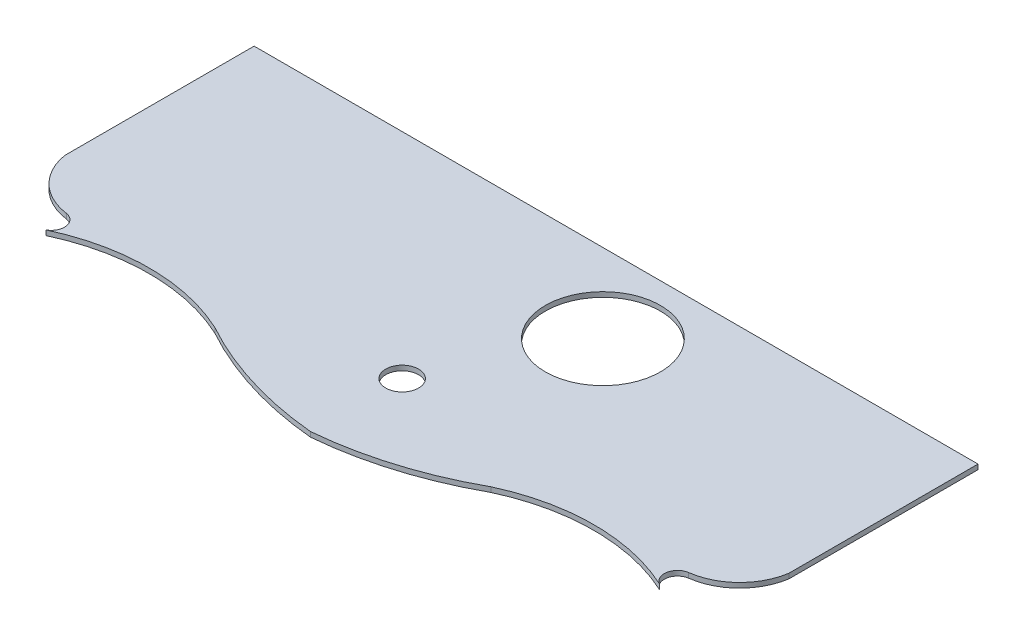
SolidWorks part; units mm, degrees
ref_plane "Front Plane" through (0, 0, 0) normal (0, 0, 1) x (1, 0, 0)
ref_plane "Top Plane" through (0, 0, 0) normal (0, 1, 0) x (1, 0, 0)
ref_plane "Right Plane" through (0, 0, 0) normal (1, 0, 0) x (0, 0, -1)
ref_plane "Plane1" through (0, 22.5, 0) normal (0, 1, 0) x (1, 0, 0)
ref_plane "Plane2" through (0, 24, 0) normal (0, 1, 0) x (1, 0, 0)
sketch "Sketch2" plane through (0, 22.5, 0) normal (0, 1, 0) x (1, 0, 0)
  line L0 (0, -100) -> (0, 70) construction
  line L15 (-34.8399, -30) -> (34.8399, -30) construction
  line L16 (-110, 50) -> (110, 50)
  line L17 (0, 50) -> (0, -30) construction
  line L19 (-110, 50) -> (-110, -7.5)
  line L21 (110, 50) -> (110, -7.5)
  arc A1 (94.5, -22.5368) -> (93.25, -30) centre (95.1559, -26.4829) ccw
  arc A3 (110, -7.5) -> (94.5, -22.5368) centre (92.222, -4.6815) cw
  arc A7 (93.25, -30) -> (41.9625, -30) centre (67.6063, -85.0296) ccw
  arc A9 (93.25, -30) -> (41.9625, -30) centre (67.6063, -85.0296) ccw construction
  arc A11 (41.9625, -30) -> (0, -42.8761) centre (-9.5248, 62.9793) cw
  circle A12 centre (20, 26) radius 17.5
  circle A13 centre (20, 26) radius 17.5 construction
  circle A14 centre (0, -15) radius 5
  circle A15 centre (0, -15) radius 5 construction
  arc A17 (0, -42.8761) -> (41.9625, -30) centre (-9.5248, 62.9793) ccw construction
  arc A18 (-41.9625, -30) -> (0, -42.8761) centre (9.5248, 62.9793) ccw
  arc A20 (-41.9625, -30) -> (0, -42.8761) centre (9.5248, 62.9793) ccw construction
  arc A22 (-41.9625, -30) -> (-93.25, -30) centre (-67.6063, -85.0296) ccw
  arc A24 (-41.9625, -30) -> (-93.25, -30) centre (-67.6063, -85.0296) ccw construction
  arc A25 (-110, -7.5) -> (-94.5, -22.5368) centre (-92.222, -4.6815) ccw
  arc A26 (-110, -7.5) -> (-94.5, -22.5368) centre (-92.222, -4.6815) ccw construction
  arc A27 (-94.5, -22.5368) -> (-93.25, -30) centre (-95.1559, -26.4829) cw
  arc A28 (-93.25, -30) -> (-94.5, -22.5368) centre (-95.1559, -26.4829) ccw construction
  point P0 (0, 10.0408)
extrude "Boss-Extrude2" add sketch "Sketch2" along normal up to surface (1.5 mm away) up to plane "Plane2"
